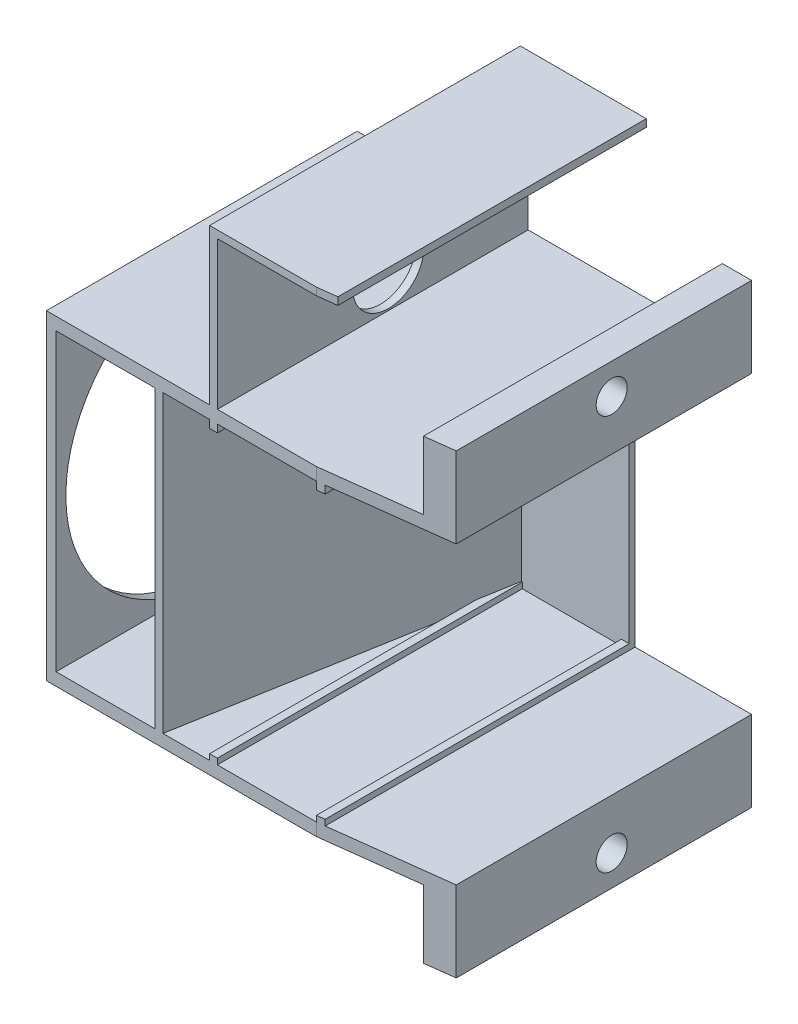
SolidWorks part; units mm, degrees
ref_plane "前视基准面" through (0, 0, 0) normal (0, 0, 1) x (1, 0, 0)
ref_plane "上视基准面" through (0, 0, 0) normal (0, 1, 0) x (1, 0, 0)
ref_plane "右视基准面" through (0, 0, 0) normal (1, 0, 0) x (0, 0, -1)
sketch "草图1" plane through (0, 0, 0) normal (0, 0, 1) x (1, 0, 0)
  line L0 (-40.6, 16.5) -> (14.319, 16.5) construction
  line L1 (-3, 0) -> (-40.6, 0)
  line L2 (0, 0) -> (0, 33)
  line L3 (-3, 33) -> (-23, 33)
  line L4 (-40.6, 0) -> (-40.6, 33)
  line L5 (-12, 31.7) -> (0, 31.7)
  line L6 (-12, 31.7) -> (-12, 30.9)
  line L7 (-12, 1.3) -> (0, 1.3)
  line L8 (-23.8, 1.9) -> (-23.8, 1.3)
  line L9 (-12.8, 31.7) -> (-23, 31.7)
  line L10 (-12.8, 31.7) -> (-12.8, 30.9)
  line L11 (-12.8, 1.3) -> (-23, 1.3)
  line L12 (-23, 31.7) -> (-23, 30.9)
  line L13 (-23.8, 31.7) -> (-28.8, 31.7)
  line L14 (-23.8, 31.7) -> (-23.8, 30.9)
  line L15 (-23.8, 1.3) -> (-28.8, 1.3)
  line L16 (0, 0) -> (0, -7)
  line L17 (-29.4, 31.7) -> (-39.6, 31.7)
  line L18 (-23.8, 33) -> (-40.6, 33)
  line L19 (-29.4, 1.3) -> (-39.6, 1.3)
  line L20 (-39.6, 31.7) -> (-39.6, 1.3)
  line L21 (-23.8, 30.9) -> (-23, 30.9)
  line L22 (-12.8, 30.9) -> (-12, 30.9)
  line L23 (-23.8, 1.9) -> (-23, 1.9)
  line L24 (-12.8, 1.9) -> (-12, 1.9)
  line L25 (-23, 1.9) -> (-23, 1.3)
  line L26 (-12.8, 1.9) -> (-12.8, 1.3)
  line L27 (-12, 1.9) -> (-12, 1.3)
  line L28 (-29.4, 31.7) -> (-28.8, 31.7)
  line L29 (-29.4, 1.3) -> (-28.8, 1.3)
  line L30 (-28.8, 1.3) -> (-28.7345, 1.3132)
  line L31 (0, 33) -> (0, 40)
  line L32 (0, 40) -> (-3, 40)
  line L33 (-3, 33) -> (-3, 40)
  line L34 (-3, 0) -> (-3, -7)
  line L35 (0, -7) -> (-3, -7)
  line L36 (-10.8364, 49) -> (-23.8, 49)
  line L37 (-23.8, 33) -> (-23.8, 48.226)
  line L38 (-23.8, 48.226) -> (-23.8, 49)
  line L39 (-23, 33) -> (-23, 48.226)
  line L42 (-23, 48.226) -> (-10.8364, 48.226)
  line L43 (-10.8364, 49) -> (-10.8364, 48.226)
  dimension "D1" = 33
  dimension "D2" = 30.4
  dimension "40" = 40.6
  dimension "D3" = 12
  dimension "D4" = 10.2
  dimension "D5" = 0.8
  dimension "D6" = 5
  dimension "D7" = 0.8
  dimension "D8" = 10.2
  dimension "D9" = 47
  dimension "D10" = 0.6
  dimension "D11" = 0.8
  dimension "D12" = 3
  dimension "D13" = 16
  dimension "D14" = 12.9636
extrude "凸台-拉伸1" add sketch "草图1" along normal blind 32 contours L4 L0 L20 L17 L28 L13 L14 L21 L12 L9 L10 L22 L6 L5 L2 L31 L32 L33 L3 | L0 L4 L1 L34 L35 L16 L2 L7 L27 L24 L26 L11 L25 L23 L8 L15 L29 L19 L20
sketch "草图2" plane through (0, 31.7, 0) normal (0, -1, 0) x (1, 0, 0)
  line L0 (-23.8, 0) -> (-29.4, 32)
  line L2 (-3, 32) -> (-40.6, 32) construction
  line L3 (-29.4, 32) -> (-28.6, 32)
  line L4 (-28.6, 32) -> (-23, 0)
  line L5 (-23, 0) -> (-23.8, 0)
  dimension "D1" = 10.2
extrude "凸台-拉伸2" add sketch "草图2" along direction (0, -1, 0) on the side of the normal up to next (30.4 mm away)
sketch "草图3" plane through (0, 31.7, 0) normal (0, -1, 0) x (1, 0, 0)
  line L0 (-3, 0) -> (-40.6, 0) construction
  line L1 (-29.4, 32) -> (-28.6, 32)
  line L2 (-29.4, 32) -> (-29.4, 0)
  line L3 (-29.4, 0) -> (-28.6, 0)
  line L4 (-28.6, 32) -> (-28.6, 0)
extrude "凸台-拉伸3" add sketch "草图3" along normal blind 0.6
sketch "草图4" plane through (0, 1.3, 0) normal (0, 1, 0) x (1, 0, 0)
  line L1 (-29.4, 0) -> (-28.6, 0)
  line L2 (-29.4, 0) -> (-29.4, -32)
  line L3 (-29.4, -32) -> (-28.6, -32)
  line L4 (-28.6, 0) -> (-28.6, -32)
extrude "凸台-拉伸4" add sketch "草图4" along normal blind 0.6
sketch "草图5" plane through (0, 0, 0) normal (0, 0, -1) x (-1, 0, 0)
  line L0 (23.8, 1.3) -> (28.6, 1.3) construction
  line L1 (12, 31.7) -> (23.8, 31.7)
  line L2 (12, 31.7) -> (12, 1.3)
  line L3 (12, 1.3) -> (23.8, 1.3)
  line L4 (23.8, 31.7) -> (23.8, 1.3)
  line L6 (39.6, 31.7) -> (39.6, 1.3) construction
  line L7 (28.6, 31.7) -> (39.6, 31.7)
  line L8 (28.6, 31.7) -> (28.6, 1.3)
  line L9 (28.6, 1.3) -> (39.6, 1.3)
  line L10 (39.6, 31.7) -> (39.6, 1.3)
extrude "凸台-拉伸11" add sketch "草图5" against normal blind 0.6
sketch "草图6" plane through (-3, 0, 0) normal (-1, 0, 0) x (0, 0, 1)
  line L0 (0, 16.5) -> (21.4256, 16.5) construction
  line L1 (0, 0) -> (0, 33) construction
  line L2 (16, 33) -> (16, -7) construction
  line L3 (0, 16.5) -> (32, 16.5) construction
  line L4 (0, 0) -> (0, 33) construction
  line L6 (32, 33) -> (0, 33) construction
  line L7 (32, -7) -> (0, -7) construction
  circle A0 centre (14.4, 36.855) radius 1.6
  circle A1 centre (14.4, -3.855) radius 1.6
  dimension "D1" = 1.6
extrude "切除-拉伸1" cut sketch "草图6" against normal through all
sketch "草图7" plane through (-40.6, 0, 0) normal (-1, 0, 0) x (0, 0, 1)
  line L0 (0, 16.5) -> (32, 16.5) construction
  line L1 (0, 0) -> (0, 33) construction
  line L2 (32, 0) -> (32, 33) construction
  line L3 (16, 33) -> (16, 0) construction
  line L4 (32, 33) -> (0, 33) construction
  line L5 (32, 0) -> (0, 0) construction
  circle A0 centre (16, 16.5) radius 15
  dimension "D1" = 30
extrude "切除-拉伸2" cut sketch "草图7" against normal blind 3
sketch "草图8" plane through (-23.8, 0, 0) normal (-1, 0, 0) x (0, 0, 1)
  circle A0 centre (14.4, 36.855) radius 3.6759
extrude "切除-拉伸3" cut sketch "草图8" against normal blind 10
sketch "草图9" plane through (0, -7, 0) normal (0, -1, 0) x (1, 0, 0)
  line L0 (-12.8, 32) -> (0.0691, 32)
  line L1 (0.0691, 32) -> (0.0691, 30.4)
  line L2 (0.0691, 30.4) -> (-12.8, 32)
  dimension "D1" = 1.6
extrude "切除-拉伸4" cut sketch "草图9" against normal through all
